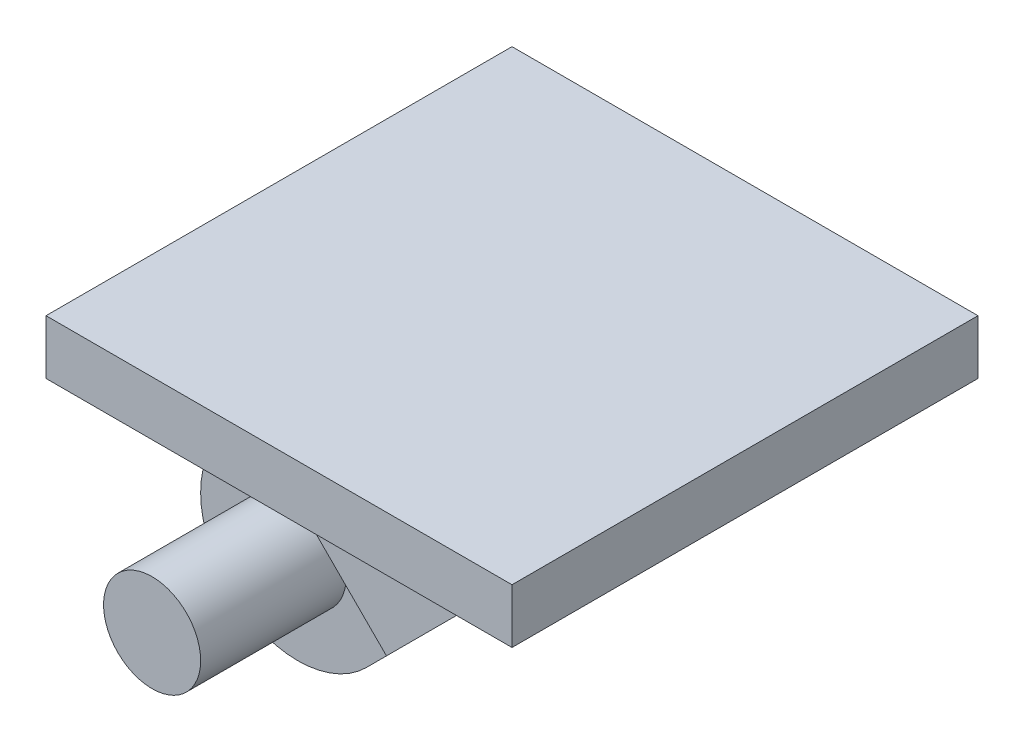
SolidWorks part; units mm, degrees
ref_plane "前视基准面" through (0, 0, 0) normal (0, 0, 1) x (1, 0, 0)
ref_plane "上视基准面" through (0, 0, 0) normal (0, 1, 0) x (1, 0, 0)
ref_plane "右视基准面" through (0, 0, 0) normal (1, 0, 0) x (0, 0, -1)
other "Configuration Table"
sketch "草图1" plane through (0, 0, 0) normal (0, 1, 0) x (1, 0, 0)
  line L1 (-30, -30) -> (30, -30)
  line L2 (-30, -30) -> (-30, 30)
  line L3 (-30, 30) -> (30, 30)
  line L4 (30, -30) -> (30, 30)
  line L5 (-30, -30) -> (30, 30) construction
  line L6 (-30, 30) -> (30, -30) construction
  point P0 (0, 0)
  dimension "D1" = 60
  dimension "D2" = 60
extrude "凸台-拉伸1" add sketch "草图1" along normal blind 7
sketch "草图2" plane through (0, 0, 0) normal (0, 0, 1) x (1, 0, 0)
  line L0 (-12.5, 0) -> (12.5, 0)
  line L1 (-30, 0) -> (30, 0) construction
  line L2 (-12.5, 0) -> (5.1777, -17.6777) construction
  line L3 (-12.5, 0) -> (-30.1777, -17.6777)
  line L4 (-30.1777, -17.6777) -> (-12.5, -35.3553) construction
  line L5 (-12.5, -35.3553) -> (5.1777, -17.6777)
  arc A0 (5.1777, -17.6777) -> (12.5, 0) centre (-12.5, 0) ccw
  arc A1 (-30.1777, -17.6777) -> (-12.5, -35.3553) centre (-21.3388, -26.5165) ccw
  point P6 (0, 0)
  dimension "D1" = 25
  dimension "D2" = 45
  dimension "D3" = 25
extrude "凸台-拉伸2" add sketch "草图2" along normal blind 12.5 and the other way blind 12.5
sketch "草图3" plane through (0, 0, 0) normal (0, 0, 1) x (1, 0, 0)
  line L0 (-21.3388, -8.8388) -> (-3.6612, -26.5165)
  line L1 (-12.5, 0) -> (-30.1777, -17.6777) construction
  line L2 (-12.5, -35.3553) -> (5.1777, -17.6777) construction
  line L3 (12.5, 0) -> (-12.5, 0) construction
  line L6 (-21.3388, -8.8388) -> (-30.1777, -17.6777)
  line L7 (-3.6612, -26.5165) -> (-12.5, -35.3553)
  arc A0 (-30.1777, -17.6777) -> (-12.5, -35.3553) centre (-21.3388, -26.5165) ccw
  dimension "D2" = 45
extrude "切除-拉伸1" cut sketch "草图3" along normal blind 6.25 from surface at -12.5 starting at face at (-8.9161, -16.0556, -12.5)
sketch "草图4" plane through (0, 0, 0) normal (0, 0, 1) x (1, 0, 0)
  line L3 (-3.6612, -26.5165) -> (-21.3388, -8.8388)
  line L4 (-12.5, -35.3553) -> (-3.6612, -26.5165)
  line L5 (-21.3388, -8.8388) -> (-30.1777, -17.6777)
  line L6 (-3.6612, -26.5165) -> (-21.3388, -8.8388)
  line L7 (-12.5, -35.3553) -> (-3.6612, -26.5165)
  line L8 (-21.3388, -8.8388) -> (-30.1777, -17.6777)
  arc A1 (-30.1777, -17.6777) -> (-12.5, -35.3553) centre (-21.3388, -26.5165) ccw
  arc A2 (-30.1777, -17.6777) -> (-12.5, -35.3553) centre (-21.3388, -26.5165) ccw
  dimension "D1" = 0
extrude "切除-拉伸2" cut sketch "草图4" against normal blind 6.25 from surface at 12.5 starting at face at (-8.9161, -16.0556, 12.5)
sketch "草图5" plane through (0, 0, 0) normal (0, 0, 1) x (1, 0, 0)
  circle A0 centre (-21.3388, -26.5165) radius 6.25
  dimension "D1" = 12.5
extrude "凸台-拉伸3" add sketch "草图5" along normal blind 25 and the other way blind 25
ref_plane "基准面1" through (2.5888, -2.5888, 0) normal (0.7071, -0.7071, 0) x (-0.7071, -0.7071, 0)
